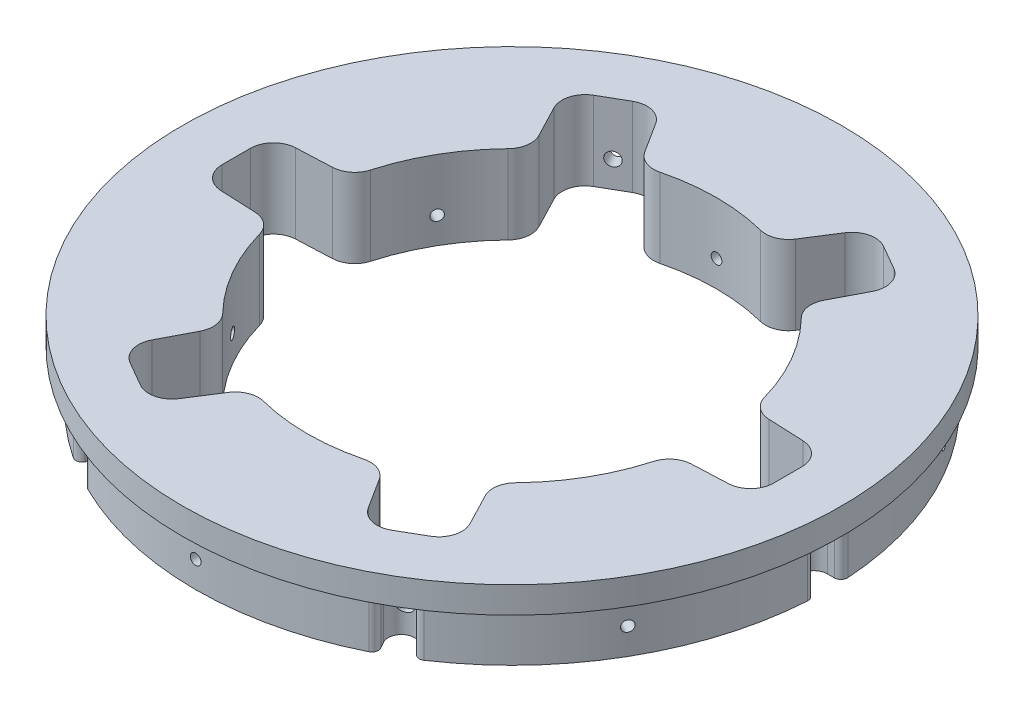
SolidWorks part; units mm, degrees
material "6061-T6 (SS)"
ref_plane "Front Plane" through (0, 0, 0) normal (0, 0, 1) x (1, 0, 0)
ref_plane "Top Plane" through (0, 0, 0) normal (0, 1, 0) x (1, 0, 0)
ref_plane "Right Plane" through (0, 0, 0) normal (1, 0, 0) x (0, 0, -1)
sketch "Sketch1" plane through (0, 0, 0) normal (0, 1, 0) x (1, 0, 0)
  circle A0 centre (0, 0) radius 76.2
  circle A1 centre (0, 0) radius 49.276
  dimension "D1" = 152.4
  dimension "D2" = 98.552
extrude "Boss-Extrude1" add sketch "Sketch1" against normal blind 19.05
sketch "Sketch3" plane through (0, -19.05, 0) normal (0, -1, 0) x (-1, 0, 0)
  line L0 (-76.1338, 3.175) -> (-72.771, 3.175)
  line L1 (-76.1338, -3.175) -> (-72.771, -3.175)
  circle A0 centre (0, 0) radius 76.2 construction
  arc A1 (-72.771, 3.175) -> (-72.771, -3.175) centre (-72.771, 0) cw
  arc A2 (-76.1338, -3.175) -> (-76.1338, 3.175) centre (0, 0) cw
  point P9 (-69.596, 0)
  point P13 (-76.2, 0)
  dimension "D1" = 6.35
  dimension "D2" = 6.604
extrude "Cut-Extrude1" cut sketch "Sketch3" against normal blind 12.7
sketch "Sketch4" plane through (0, -19.05, 0) normal (0, -1, 0) x (-1, 0, 0)
  line L0 (-66.421, 8.7312) -> (-66.421, -8.7312)
  line L1 (-66.421, -8.7312) -> (-48.3466, -9.525)
  line L2 (-48.3466, -9.525) -> (-48.3466, 9.525)
  line L3 (-48.3466, 9.525) -> (-66.421, 8.7312)
  line L4 (-66.421, 0) -> (0, 0) construction
  circle A0 centre (0, 0) radius 49.276 construction
  dimension "D1" = 3.175
  dimension "D2" = 19.05
  dimension "D3" = 17.4625
extrude "Cut-Extrude2" cut sketch "Sketch4" against normal through all
hole_wizard "#30 (0.1285) Diameter Hole1" positions "Sketch5" profile "Sketch6" hole size "#30" standard "ANSI Inch"
sketch "Sketch5" plane through (66.421, 0, 0) normal (-1, 0, 0) x (0, 0, 1)
  line L0 (-8.7312, -19.05) -> (8.7312, -19.05) construction
  point P0 (0, -12.7)
  dimension "D1" = 6.35
sketch "Sketch6" plane through (66.421, -12.7, 0) normal (0, 1, 0) x (0, 0, 1)
  line L0 (0, 0) -> (0, 9.779)
  line L1 (0, 9.779) -> (1.6319, 9.779)
  line L2 (1.6319, 9.779) -> (1.6319, 0)
  line L5 (1.6319, 0) -> (0, 0)
  line L11 (0, -6.35) -> (0, 107.95) construction
  dimension "Thru Hole Dia." = 3.2639
  dimension "Thru Hole Depth" = 9.779
fillet "Fillet1" radius 1.5875 2 edges at (76.1338, -12.7, 3.175) (76.1338, -12.7, -3.175)
fillet "Fillet2" radius 5.5562 4 edges at (66.421, -9.525, 8.7312) (66.421, -9.525, -8.7312) (48.3466, -9.525, 9.525) (48.3466, -9.525, -9.525)
sketch "Sketch11" plane through (0, 0, 0) normal (0, 0, 1) x (1, 0, 0)
  line L0 (-76.2, -19.05) -> (76.0446, -19.05) construction
  circle A0 centre (0, -12.7) radius 1.2891
  dimension "D1" = 2.5781
  dimension "D2" = 6.35
extrude "Cut-Extrude4" cut sketch "Sketch11" against normal through all
pattern_circular "CirPattern1" count 6 over 360 about axis through (0, 0, 0) along (0, 1, 0) of "Cut-Extrude1", "Cut-Extrude2", "Fillet2", "Fillet1", "#30 (0.1285) Diameter Hole1", "Cut-Extrude4"
sketch "Sketch8" plane through (0, 0, 0) normal (0, 1, 0) x (1, 0, 0)
  circle A0 centre (0, 0) radius 79.375
  circle A1 centre (0, 0) radius 76.2
  circle A2 centre (0, 0) radius 76.2 construction
  dimension "D1" = 3.175
extrude "Boss-Extrude3" add sketch "Sketch8" against normal up to surface (6.35 mm away) up to face at (-74.0439, -6.35, 0)
